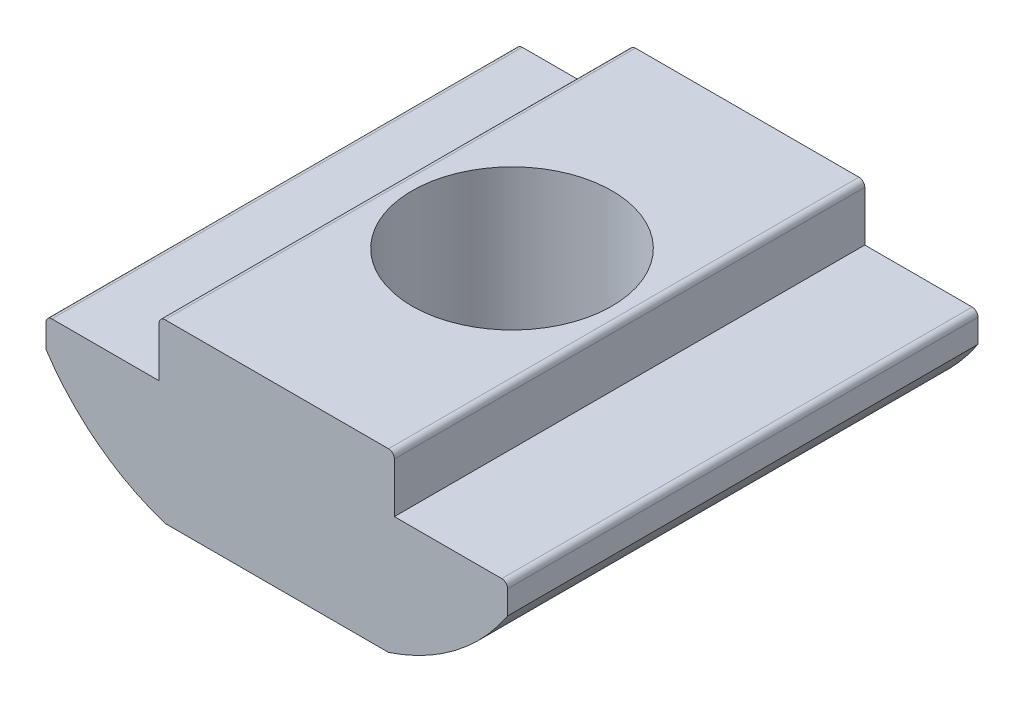
SolidWorks part; units mm, degrees
ref_plane "前视基准面" through (0, 0, 0) normal (0, 0, 1) x (1, 0, 0)
ref_plane "上视基准面" through (0, 0, 0) normal (0, 1, 0) x (1, 0, 0)
ref_plane "右视基准面" through (0, 0, 0) normal (1, 0, 0) x (0, 0, -1)
sketch "草图1" plane through (0, 0, 0) normal (0, 0, 1) x (1, 0, 0)
  line B0 (3.8, 0) -> (-3.8, 0)
  line B1 (-7.85, 3.9) -> (-7.85, 3.1)
  line B2 (7.85, 3.9) -> (7.85, 3.1)
  line B3 (-3.8, 6) -> (3.8, 6)
  line B4 (-7.65, 4.1) -> (-4, 4.1)
  line B5 (4, 4.1) -> (7.65, 4.1)
  line B6 (-4, 5.8) -> (-4, 4.1)
  line B7 (4, 5.8) -> (4, 4.1)
  arc B8 (-3.8, 6) -> (-4, 5.8) centre (-3.8, 5.8) ccw
  arc B9 (4, 5.8) -> (3.8, 6) centre (3.8, 5.8) ccw
  arc B10 (-7.65, 4.1) -> (-7.85, 3.9) centre (-7.65, 3.9) ccw
  arc B11 (7.85, 3.9) -> (7.65, 4.1) centre (7.65, 3.9) ccw
  arc B12 (-7.85, 3.1) -> (-3.8, 0) centre (-1.38, 7.3572) ccw
  arc B13 (3.8, 0) -> (7.85, 3.1) centre (1.38, 7.3572) ccw
sketch_block_instance "A$C20D32036-1"
sketch_block "A$C20D32036"
extrude "凸台-拉伸1" add sketch "草图1" along normal mid plane 16
sketch "草图3" plane through (0, 6, 0) normal (0, 1, 0) x (1, 0, 0)
  point P0 (0, 0)
hole_wizard "M8 螺纹孔1" positions "3D草图1" profile "草图4" tap size "M8" standard "Iso"
sketch3d "3D草图1"
  point P0 (0, 6, 0)
sketch "草图4" plane through (0, 6, 0) normal (1, 0, 0) x (0, 0, 1)
  line L0 (0, 0) -> (0, 21.7929)
  line L1 (0, 21.7929) -> (3.4, 19.75)
  line L2 (3.4, 19.75) -> (3.4, 0)
  line L5 (3.4, 0) -> (0, 0)
  line L10 (0, 21.7929) -> (-3.4, 19.75) construction
  line L11 (0, -6.35) -> (0, 107.95) construction
  dimension "螺纹孔钻头直径" = 6.8
  dimension "螺纹孔钻头深度" = 19.75
  dimension "导头角度" = 118
cosmetic thread "孔螺蚊线1"
